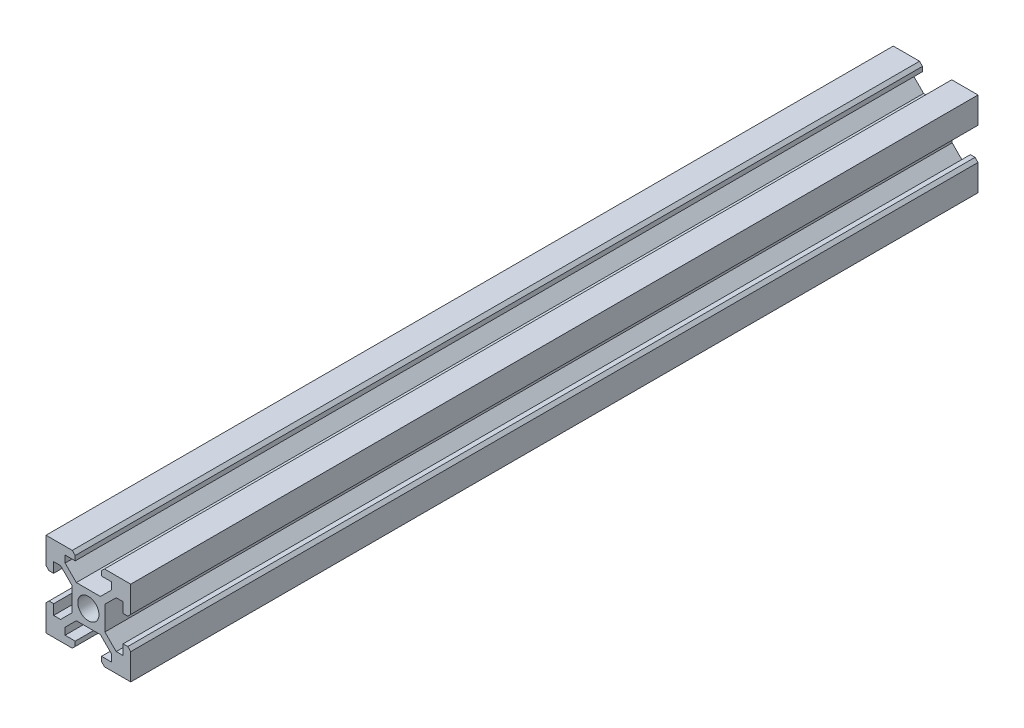
SolidWorks part; units mm, degrees
material "1060 Alloy"
ref_plane "Front Plane" through (0, 0, 0) normal (0, 0, 1) x (1, 0, 0)
ref_plane "Top Plane" through (0, 0, 0) normal (0, 1, 0) x (1, 0, 0)
ref_plane "Right Plane" through (0, 0, 0) normal (1, 0, 0) x (0, 0, -1)
sketch "Sketch1" plane through (0, 0, 0) normal (0, 0, 1) x (1, 0, 0)
  line L0 (3.9, -2.8393) -> (6.5607, -5.5)
  line L1 (-10, 10) -> (10, 10) construction
  line L2 (-10, 10) -> (-10, -10) construction
  line L3 (-10, -10) -> (10, -10) construction
  line L4 (10, 10) -> (10, -10) construction
  line L5 (-10, 10) -> (10, -10) construction
  line L6 (-10, -10) -> (10, 10) construction
  line L7 (-3.9, -3.9) -> (3.9, -3.9) construction
  line L8 (-3.9, -3.9) -> (-3.9, 3.9) construction
  line L9 (-3.9, 3.9) -> (3.9, 3.9) construction
  line L10 (3.9, -3.9) -> (3.9, 3.9) construction
  line L11 (-3.9, -3.9) -> (3.9, 3.9) construction
  line L12 (-3.9, 3.9) -> (3.9, -3.9) construction
  line L13 (-10, 10) -> (-5.5, 10) construction
  line L14 (-10, 10) -> (-10, 5.5) construction
  line L15 (-10, 5.5) -> (-5.5, 5.5) construction
  line L16 (-5.5, 10) -> (-5.5, 5.5) construction
  line L17 (10, 10) -> (5.5, 10) construction
  line L18 (10, 10) -> (10, 5.5) construction
  line L19 (10, 5.5) -> (5.5, 5.5) construction
  line L20 (5.5, 10) -> (5.5, 5.5) construction
  line L21 (-10, -10) -> (-5.5, -10) construction
  line L22 (-10, -10) -> (-10, -5.5) construction
  line L23 (-10, -5.5) -> (-5.5, -5.5) construction
  line L24 (-5.5, -10) -> (-5.5, -5.5) construction
  line L25 (10, -10) -> (5.5, -10) construction
  line L26 (10, -10) -> (10, -5.5) construction
  line L27 (10, -5.5) -> (5.5, -5.5) construction
  line L28 (5.5, -10) -> (5.5, -5.5) construction
  line L29 (2.8393, -3.9) -> (5.5, -6.5607)
  line L30 (-5.5, 6.5607) -> (-2.8393, 3.9)
  line L31 (-6.5607, 5.5) -> (-3.9, 2.8393)
  line L32 (5.5, 6.5607) -> (2.8393, 3.9)
  line L33 (6.5607, 5.5) -> (3.9, 2.8393)
  line L34 (-6.5607, -5.5) -> (-3.9, -2.8393)
  line L35 (-5.5, -6.5607) -> (-2.8393, -3.9)
  line L36 (-2.8393, 3.9) -> (2.8393, 3.9)
  line L37 (-3.9, 2.8393) -> (-3.9, -2.8393)
  line L38 (-2.8393, -3.9) -> (2.8393, -3.9)
  line L39 (3.9, -2.8393) -> (3.9, 2.8393)
  line L40 (5.5, 6.5607) -> (5.5, 8.2007)
  line L41 (5.5, 8.2007) -> (3.1, 8.2007)
  line L42 (3.1, 8.2007) -> (3.1, 9.3)
  line L43 (3.1, 9.3) -> (3.8, 10)
  line L44 (3.8, 10) -> (10, 10)
  line L45 (10, 10) -> (10, 3.8)
  line L46 (10, 3.8) -> (9.3, 3.1)
  line L47 (9.3, 3.1) -> (8.2007, 3.1)
  line L48 (8.2007, 3.1) -> (8.2007, 5.5)
  line L49 (8.2007, 5.5) -> (6.5607, 5.5)
  line L50 (3.1, -8.2007) -> (5.5, -8.2007)
  line L51 (3.1, -9.3) -> (3.1, -8.2007)
  line L52 (3.8, -10) -> (3.1, -9.3)
  line L53 (10, -10) -> (3.8, -10)
  line L54 (10, -3.8) -> (10, -10)
  line L55 (9.3, -3.1) -> (10, -3.8)
  line L56 (8.2007, -3.1) -> (9.3, -3.1)
  line L57 (8.2007, -5.5) -> (8.2007, -3.1)
  line L58 (6.5607, -5.5) -> (8.2007, -5.5)
  line L59 (5.5, -8.2007) -> (5.5, -6.5607)
  line L60 (-8.2007, -3.1) -> (-8.2007, -5.5)
  line L61 (-9.3, -3.1) -> (-8.2007, -3.1)
  line L62 (-10, -3.8) -> (-9.3, -3.1)
  line L63 (-10, -10) -> (-10, -3.8)
  line L64 (-3.8, -10) -> (-10, -10)
  line L65 (-3.1, -9.3) -> (-3.8, -10)
  line L66 (-3.1, -8.2007) -> (-3.1, -9.3)
  line L67 (-5.5, -8.2007) -> (-3.1, -8.2007)
  line L68 (-5.5, -6.5607) -> (-5.5, -8.2007)
  line L69 (-8.2007, -5.5) -> (-6.5607, -5.5)
  line L70 (-3.1, 8.2007) -> (-5.5, 8.2007)
  line L71 (-3.1, 9.3) -> (-3.1, 8.2007)
  line L72 (-3.8, 10) -> (-3.1, 9.3)
  line L73 (-10, 10) -> (-3.8, 10)
  line L74 (-10, 3.8) -> (-10, 10)
  line L75 (-9.3, 3.1) -> (-10, 3.8)
  line L76 (-8.2007, 3.1) -> (-9.3, 3.1)
  line L77 (-8.2007, 5.5) -> (-8.2007, 3.1)
  line L78 (-6.5607, 5.5) -> (-8.2007, 5.5)
  line L79 (-5.5, 8.2007) -> (-5.5, 6.5607)
  circle A0 centre (0, 0) radius 2.5
  point P83 (0, 0)
  dimension "D1" = 5
  dimension "D2" = 20
  dimension "D3" = 7.8
  dimension "D4" = 4.5
  dimension "D5" = 1.5
  dimension "D6" = 0.75
  dimension "D7" = 1.5
  dimension "D8" = 0.75
  dimension "D9" = 1.5
  dimension "D10" = 0.75
  dimension "D11" = 1.5
  dimension "D12" = 0.75
  dimension "D13" = 1.64
  dimension "D14" = 45
  dimension "D15" = 3.1
  dimension "D16" = 6.2
  dimension "D17" = 6.2
  dimension "D18" = 3.1
  dimension "D19" = 4
extrude "Boss-Extrude1" add sketch "Sketch1" along normal mid plane 200 contours L79 L70 L71 L72 L73 L74 L75 L76 L77 L78 L31 L37 L34 L69 L60 L61 L62 L63 L64 L65 L66 L67 L68 L35 L38 L29 L59 L50 L51 L52 L53 L54 L55 L56 L57 L58 L0 L39 L33 L49 L48 L47 L46 L45 L44 L43 L42 L41 L40 L32 L36
